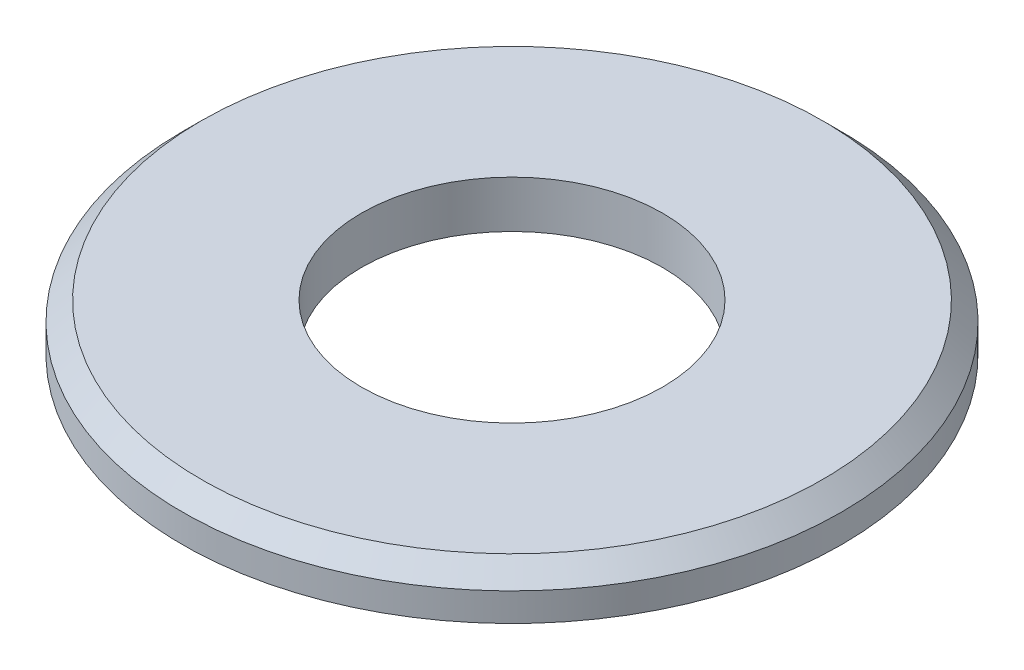
SolidWorks part; units mm, degrees
ref_plane "Alzado" through (0, 0, 0) normal (0, 0, 1) x (1, 0, 0)
ref_plane "Planta" through (0, 0, 0) normal (0, 1, 0) x (1, 0, 0)
ref_plane "Vista lateral" through (0, 0, 0) normal (1, 0, 0) x (0, 0, -1)
sketch "Croquis2" plane through (0, 0, 0) normal (0, 0, 1) x (1, 0, 0)
  line L0 (0, 10.1957) -> (0, -10.1957) construction
  line L1 (0, 10.1957) -> (0, 9.6957)
  line L2 (0, 10.1957) -> (0, 9.6957) construction
  line L3 (0, 9.6957) -> (-3.5, 9.6957)
  line L4 (-3.5, 9.6957) -> (-3.5, 9.9957)
  line L5 (-3.3, 10.1957) -> (0, 10.1957)
  line L6 (0, 9.6957) -> (0, 10.1957)
  line L7 (-3.5, 9.9957) -> (-3.3, 10.1957)
  point P4 (0, 0)
  dimension "D1" = 0.2
  dimension "D2" = 0.5
  dimension "D3" = 3.5
  dimension "D5" = 45
revolve "Revolución1" add sketch "Croquis2" angle 360 about L0
sketch "Croquis3" plane through (0, 10.1957, 0) normal (0, 1, 0) x (1, 0, 0)
  circle A0 centre (0, 0) radius 1.6
  dimension "D1" = 3.2
extrude "Cortar-Extruir1" cut sketch "Croquis3" against normal through all
